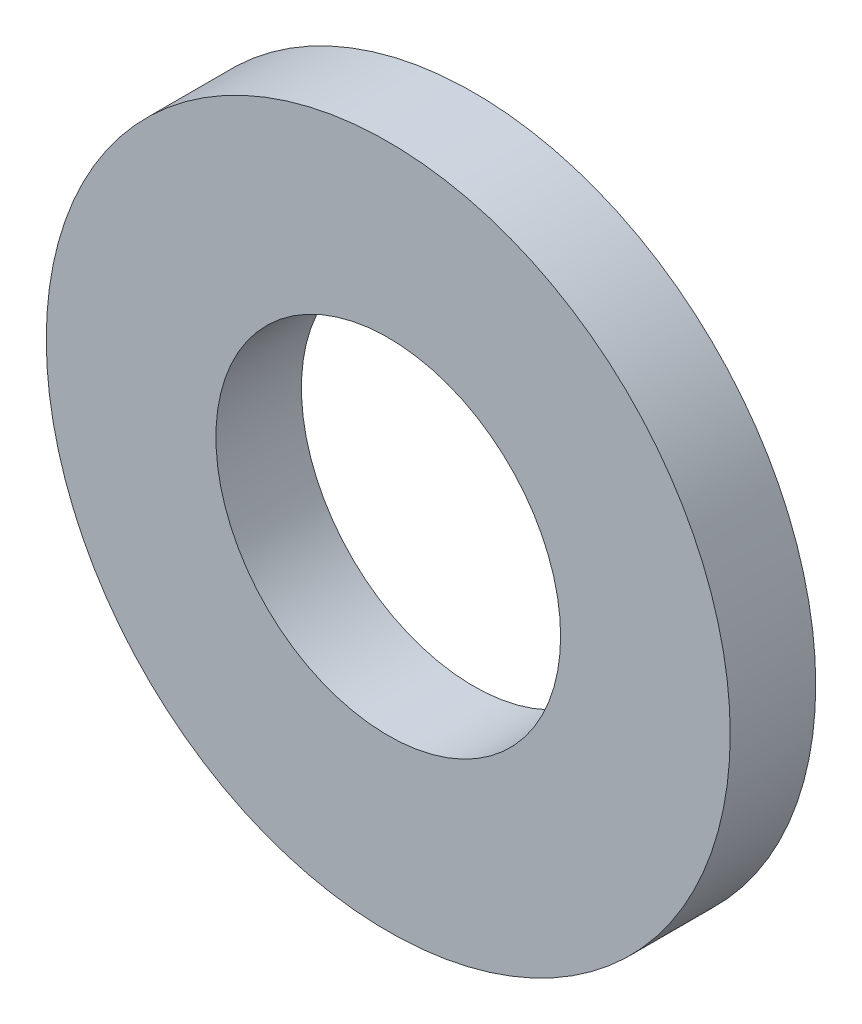
SolidWorks part; units mm, degrees
ref_plane "Front Plane" through (0, 0, 0) normal (0, 0, 1) x (1, 0, 0)
ref_plane "Top Plane" through (0, 0, 0) normal (0, 1, 0) x (1, 0, 0)
ref_plane "Right Plane" through (0, 0, 0) normal (1, 0, 0) x (0, 0, -1)
sketch "Sketch1" plane through (0, 0, 0) normal (0, 0, 1) x (1, 0, 0)
  circle A0 centre (0, 0) radius 6.35
  circle A1 centre (0, 0) radius 3.2004
  dimension "OD" = 12.7
  dimension "ID" = 6.4008
extrude "Extrude1" add sketch "Sketch1" along normal mid plane 1.5875
sketch "Sketch2" plane through (0, 0, 0) normal (1, 0, 0) x (0, 0, -1)
  line L0 (-0.7938, -3.2004) -> (0.7938, -3.2004) construction
  line L3 (0.7938, 3.2004) -> (-0.7938, 3.2004) construction
  line L5 (-0.7938, -3.2004) -> (0.7938, -3.2004)
  line L6 (0.7938, 3.2004) -> (-0.7938, 3.2004)
sketch "Sketch4" plane through (0, 0, 0.7937) normal (0, 0, 1) x (1, 0, 0)
  line L0 (0, 0) -> (-2.263, 2.263)
  line L1 (0, -3.4925) -> (0, 3.4925) construction
  circle A0 centre (0, 0) radius 3.2004 construction
  dimension "D1" = 45
